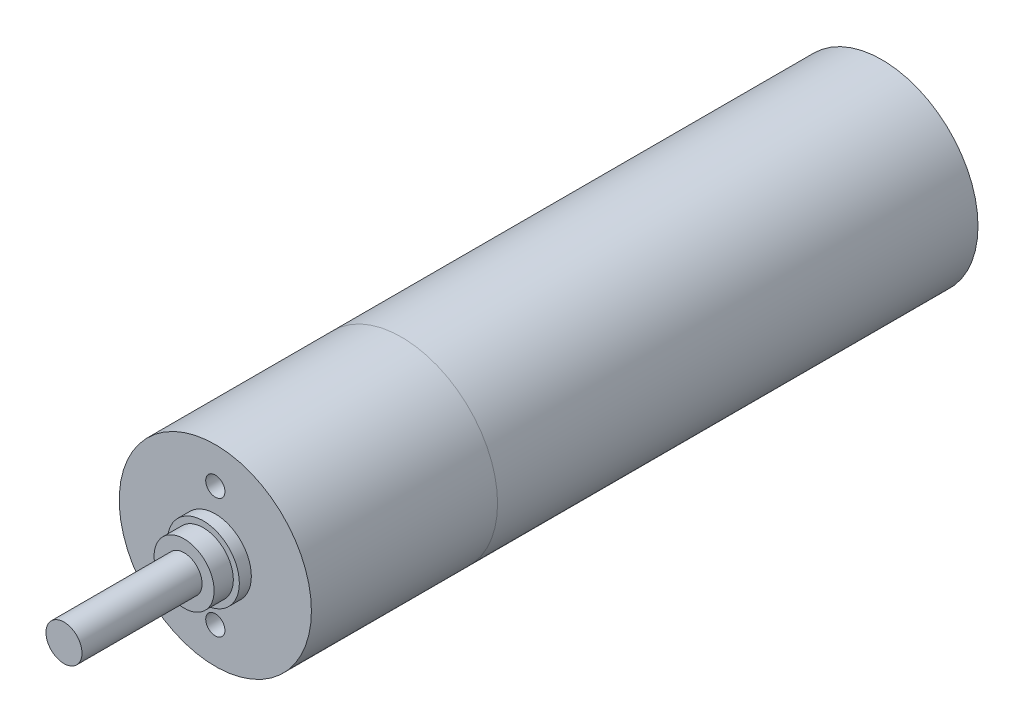
SolidWorks part; units mm, degrees
ref_plane "Front" through (0, 0, 0) normal (0, 0, 1) x (1, 0, 0)
ref_plane "Top" through (0, 0, 0) normal (0, 1, 0) x (1, 0, 0)
ref_plane "Right" through (0, 0, 0) normal (1, 0, 0) x (0, 0, -1)
sketch "Sketch1" plane through (0, 0, 0) normal (0, 0, 1) x (1, 0, 0)
  circle A0 centre (0, 0) radius 8
  dimension "D1" = 16
extrude "Extrude1" add sketch "Sketch1" along normal blind 40
sketch "Sketch2" plane through (0, 0, 40) normal (0, 0, 1) x (1, 0, 0)
  circle A0 centre (0, 0) radius 8
  dimension "D1" = 16
extrude "Extrude2" add sketch "Sketch2" along normal blind 15.5 separate body
sketch "Sketch3" plane through (0, 0, 55.5) normal (0, 0, 1) x (1, 0, 0)
  circle A0 centre (0, 0) radius 3
  dimension "D1" = 6
extrude "Extrude3" add sketch "Sketch3" along normal blind 1
sketch "Sketch4" plane through (0, 0, 56.5) normal (0, 0, 1) x (1, 0, 0)
  circle A0 centre (0, 0) radius 2.5
  dimension "D1" = 5
extrude "Extrude4" add sketch "Sketch4" along normal blind 1.6
sketch "Sketch5" plane through (0, 0, 58.1) normal (0, 0, 1) x (1, 0, 0)
  circle A0 centre (0, 0) radius 1.5
  dimension "D1" = 3
extrude "Extrude5" add sketch "Sketch5" along normal blind 10
sketch "Sketch6" plane through (0, 0, 55.5) normal (0, 0, 1) x (1, 0, 0)
  circle A0 centre (0, 5) radius 0.75
  circle A1 centre (0, -5) radius 0.75
  dimension "D1" = 1.5
  dimension "D2" = 1.5
  dimension "D3" = 5
  dimension "D4" = 5
extrude "Extrude6" cut sketch "Sketch6" against normal blind 3
hole_wizard "M2 Tapped Hole1" positions "3DSketch1" profile "Sketch7" tap size "M2" standard "DIN"
sketch3d "3DSketch1"
  line L0 (0, 5, 52.5) -> (0, 5, 55.5) construction
  line L1 (0, -5, 52.5) -> (0, -5, 55.5) construction
  point P0 (0, 5, 55.5)
  point P4 (0, -5, 55.5)
sketch "Sketch7" plane through (0, 5, 55.5) normal (1, 0, 0) x (0, -1, 0)
  line L0 (0, 0) -> (0, 3.4807)
  line L1 (0, 3.4807) -> (0.8, 3)
  line L2 (0.8, 3) -> (0.8, 0)
  line L5 (0.8, 0) -> (0, 0)
  line L10 (0, 3.4807) -> (-0.8, 3) construction
  line L11 (0, -6.35) -> (0, 107.95) construction
  dimension "Tap Drill Dia." = 1.6
  dimension "Tap Drill Depth" = 3
  dimension "Drill Angle" = 118
cosmetic thread "Hole Thread1" parameters "D1"=3, "D2"=2
cosmetic thread "Hole Thread2" parameters "D1"=3, "D2"=2
